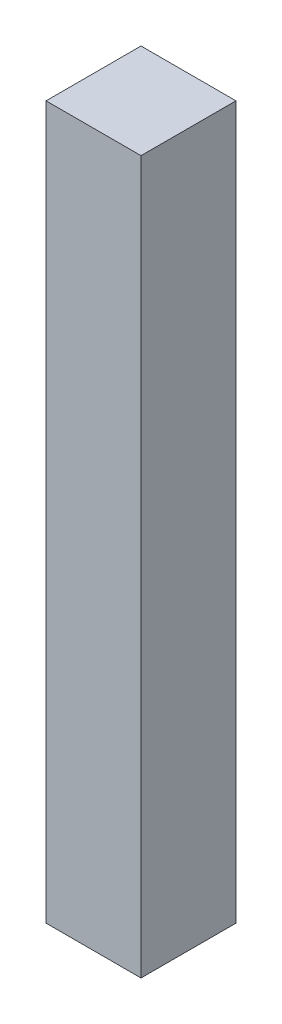
SolidWorks part; units mm, degrees
ref_plane "Front Plane" through (0, 0, 0) normal (0, 0, 1) x (1, 0, 0)
ref_plane "Top Plane" through (0, 0, 0) normal (0, 1, 0) x (1, 0, 0)
ref_plane "Right Plane" through (0, 0, 0) normal (1, 0, 0) x (0, 0, -1)
sketch "Sketch1" plane through (0, 0, 0) normal (0, 1, 0) x (1, 0, 0)
  line L1 (0, 0) -> (20, 0)
  line L2 (0, 0) -> (0, -20)
  line L3 (0, -20) -> (20, -20)
  line L4 (20, 0) -> (20, -20)
extrude "Boss-Extrude1" add sketch "Sketch1" along normal blind 150
